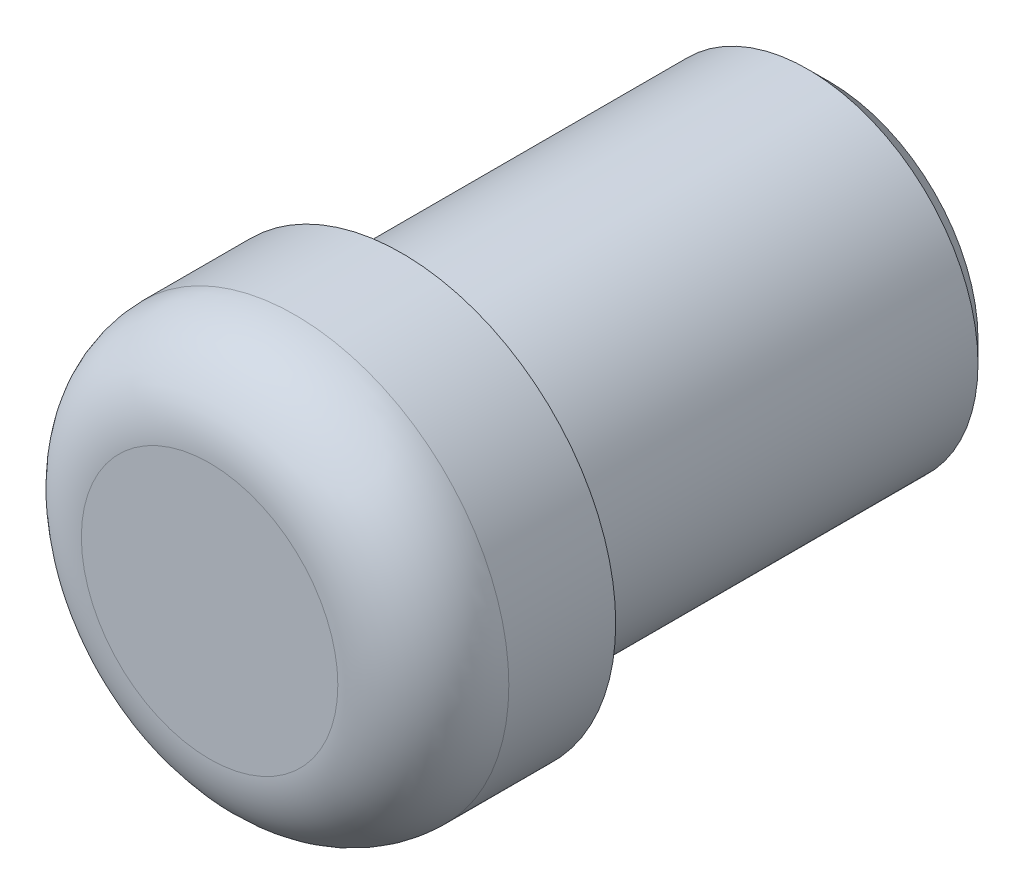
SolidWorks part; units mm, degrees
ref_plane "Front Plane" through (0, 0, 0) normal (0, 0, 1) x (1, 0, 0)
ref_plane "Top Plane" through (0, 0, 0) normal (0, 1, 0) x (1, 0, 0)
ref_plane "Right Plane" through (0, 0, 0) normal (1, 0, 0) x (0, 0, -1)
sketch "Sketch1" plane through (0, 0, 0) normal (0, 0, 1) x (1, 0, 0)
  circle A0 centre (0, 0) radius 3.975
  dimension "D1" = 7.95
extrude "Boss-Extrude1" add sketch "Sketch1" along normal blind 10
sketch "Sketch2" plane through (0, 0, 10) normal (0, 0, 1) x (1, 0, 0)
  circle A0 centre (0, 0) radius 5
  dimension "D1" = 10
extrude "Boss-Extrude2" add sketch "Sketch2" along normal blind 4.5
fillet "Fillet4" radius 2 1 edges at (5, 0, 14.5)
fillet "Fillet5" radius 0.5 1 edges at (3.975, 0, 10)
chamfer "Chamfer1" distance 0.5 angle 45 1 edges at (3.975, 0, 0)
